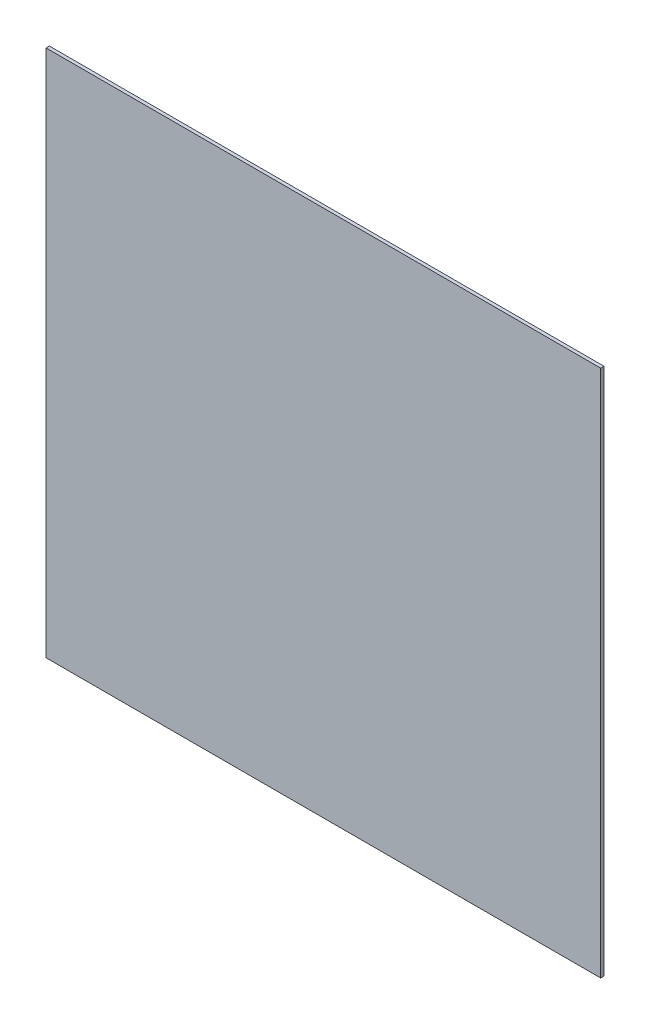
SolidWorks part; units mm, degrees
ref_plane "Alzado" through (0, 0, 0) normal (0, 0, 1) x (1, 0, 0)
ref_plane "Planta" through (0, 0, 0) normal (0, 1, 0) x (1, 0, 0)
ref_plane "Vista lateral" through (0, 0, 0) normal (1, 0, 0) x (0, 0, -1)
sketch "Croquis1" plane through (0, 0, 0) normal (0, 0, 1) x (1, 0, 0)
  line L1 (0, 0) -> (533.4, 0)
  line L2 (0, 0) -> (0, 508)
  line L3 (0, 508) -> (533.4, 508)
  line L4 (533.4, 0) -> (533.4, 508)
  dimension "D1" = 533.4
  dimension "D2" = 508
extrude "Saliente-Extruir1" add sketch "Croquis1" along normal blind 3.175
